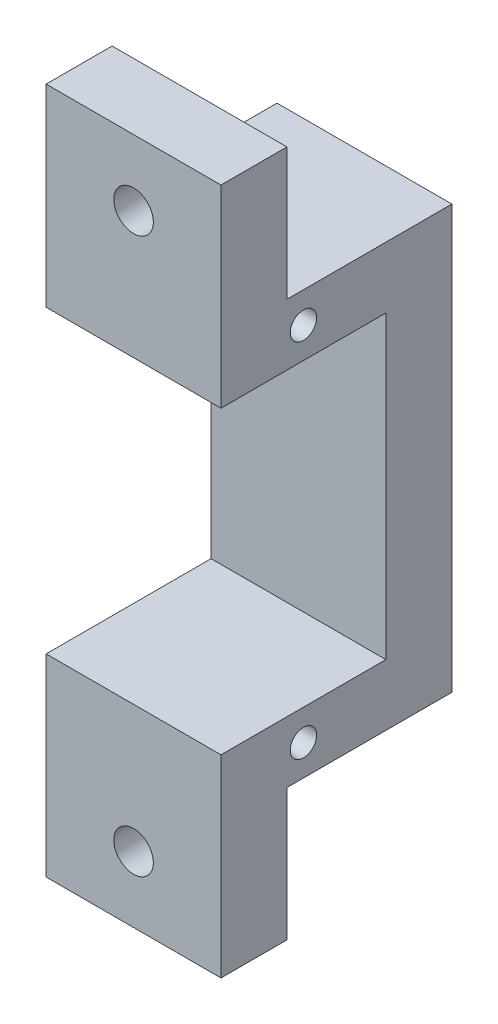
SolidWorks part; units mm, degrees
material "ABS"
ref_plane "Plano frontal" through (0, 0, 0) normal (0, 0, 1) x (1, 0, 0)
ref_plane "Plano superior" through (0, 0, 0) normal (0, 1, 0) x (1, 0, 0)
ref_plane "Plano direito" through (0, 0, 0) normal (1, 0, 0) x (0, 0, -1)
sketch "Esboço1" plane through (0, 0, 0) normal (0, 1, 0) x (1, 0, 0)
  line L1 (-21.7379, -6.1618) -> (-8.4879, -6.1618)
  line L2 (-21.7379, -6.1618) -> (-21.7379, -18.6618)
  line L3 (-21.7379, -18.6618) -> (-8.4879, -18.6618)
  line L4 (-8.4879, -6.1618) -> (-8.4879, -18.6618)
extrude "Ressalto-extrusão1" add sketch "Esboço1" against normal blind 4.65
sketch "Esboço2" plane through (0, 0, 6.1618) normal (0, 0, -1) x (-1, 0, 0)
  line L1 (21.7379, 0) -> (8.4879, 0)
  line L2 (21.7379, 0) -> (21.7379, -32.05)
  line L3 (21.7379, -32.05) -> (8.4879, -32.05)
  line L4 (8.4879, 0) -> (8.4879, -32.05)
extrude "Ressalto-extrusão2" add sketch "Esboço2" along normal blind 5
sketch "Esboço3" plane through (0, 0, 6.1618) normal (0, 0, 1) x (1, 0, 0)
  line L0 (-21.7379, -32.05) -> (-21.7379, -4.65) construction
  line L1 (-8.4879, -32.05) -> (-21.7379, -32.05)
  line L2 (-8.4879, -32.05) -> (-8.4879, -27.4)
  line L3 (-8.4879, -27.4) -> (-21.7379, -27.4)
  line L4 (-21.7379, -32.05) -> (-21.7379, -27.4)
extrude "Ressalto-extrusão3" add sketch "Esboço3" along normal blind 12.5
sketch "Esboço4" plane through (0, -32.05, 0) normal (0, -1, 0) x (-1, 0, 0)
  line L0 (8.4879, -1.1618) -> (8.4879, -18.6618) construction
  line L1 (21.7379, -18.6618) -> (8.4879, -18.6618)
  line L2 (21.7379, -18.6618) -> (21.7379, -13.6618)
  line L3 (21.7379, -13.6618) -> (8.4879, -13.6618)
  line L4 (8.4879, -18.6618) -> (8.4879, -13.6618)
extrude "Ressalto-extrusão4" add sketch "Esboço4" along normal blind 10
sketch "Esboço5" plane through (0, 0, 0) normal (0, 1, 0) x (1, 0, 0)
  line L0 (-8.4879, -18.6618) -> (-8.4879, -1.1618) construction
  line L1 (-21.7379, -18.6618) -> (-8.4879, -18.6618)
  line L2 (-21.7379, -18.6618) -> (-21.7379, -13.6618)
  line L3 (-21.7379, -13.6618) -> (-8.4879, -13.6618)
  line L4 (-8.4879, -18.6618) -> (-8.4879, -13.6618)
extrude "Ressalto-extrusão5" add sketch "Esboço5" along normal blind 10
sketch "Esboço6" plane through (0, 0, 13.6618) normal (0, 0, -1) x (-1, 0, 0)
  line L0 (8.4879, 10) -> (21.7379, 10) construction
  line L1 (21.7379, 10) -> (21.7379, 0) construction
  line L2 (21.7379, -42.05) -> (8.4879, -42.05) construction
  line L3 (21.7379, -42.05) -> (21.7379, -32.05) construction
  circle A0 centre (15.1129, 5) radius 1.5
  circle A1 centre (15.1129, -37.05) radius 1.5
  point P10 (15.1129, -42.05)
  point P13 (21.7379, -37.05)
  dimension "D1" = 5
  dimension "D2" = 6.625
  dimension "D3" = 5
  dimension "D4" = 6.625
extrude "Corte-extrusão1" cut sketch "Esboço6" against normal blind 10
sketch "Esboço7" plane through (-8.4879, 0, 0) normal (1, 0, 0) x (0, 0, -1)
  line L0 (-18.6618, -4.65) -> (-18.6618, 10) construction
  line L1 (-13.6618, 0) -> (-1.1618, 0) construction
  circle A0 centre (-12.4118, -2.325) radius 1
  dimension "D1" = 6.25
  dimension "D2" = 2.325
sketch "Esboço8" plane through (-8.4879, 0, 0) normal (1, 0, 0) x (0, 0, -1)
  line L0 (-18.6618, -42.05) -> (-18.6618, -27.4) construction
  line L1 (-1.1618, -32.05) -> (-13.6618, -32.05) construction
  circle A0 centre (-12.4118, -29.725) radius 1
  dimension "D1" = 6.25
  dimension "D2" = 2.325
extrude "Corte-extrusão2" cut sketch "Esboço7" against normal through all
extrude "Corte-extrusão3" cut sketch "Esboço8" against normal through all
